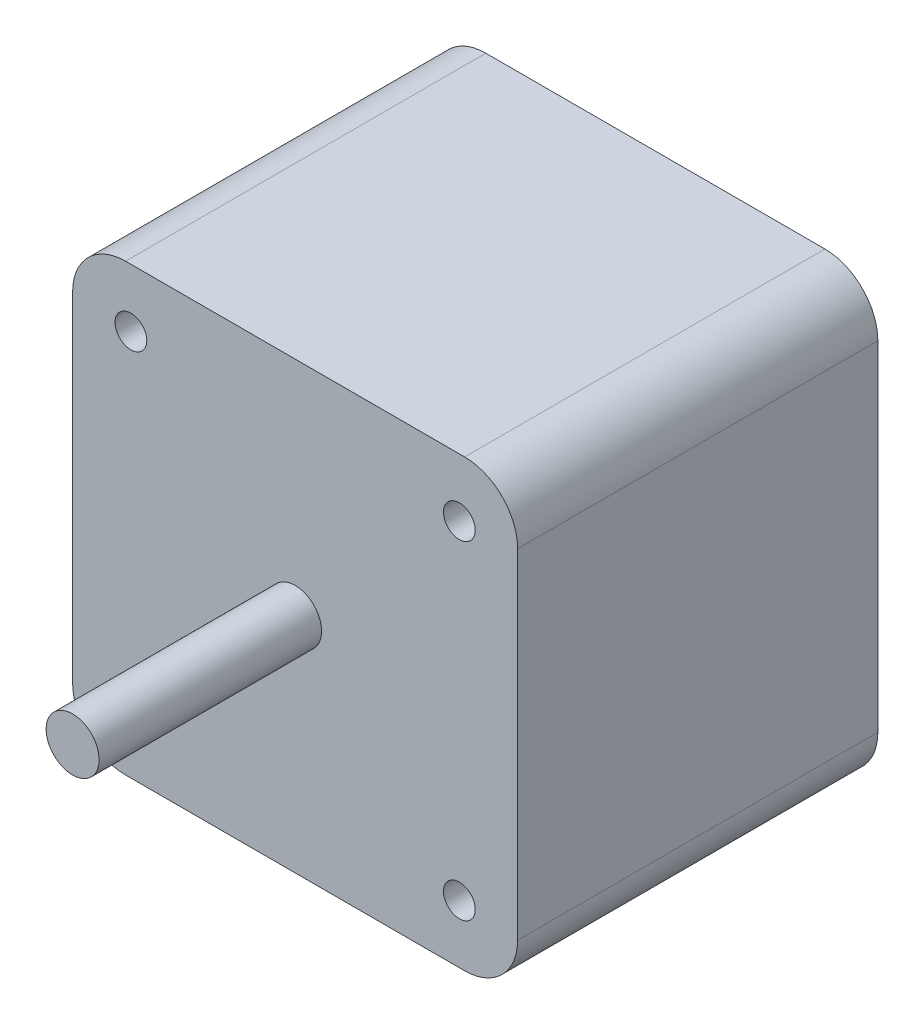
SolidWorks part; units mm, degrees
ref_plane "Płaszczyzna przednia" through (0, 0, 0) normal (0, 0, 1) x (1, 0, 0)
ref_plane "Płaszczyzna górna" through (0, 0, 0) normal (0, 1, 0) x (1, 0, 0)
ref_plane "Płaszczyzna prawa" through (0, 0, 0) normal (1, 0, 0) x (0, 0, -1)
sketch "Szkic1" plane through (0, 0, 0) normal (0, 0, 1) x (1, 0, 0)
  line L1 (-21, -21) -> (21, -21)
  line L2 (-21, -21) -> (-21, 21)
  line L3 (-21, 21) -> (21, 21)
  line L4 (21, -21) -> (21, 21)
  line L5 (-21, -21) -> (21, 21) construction
  line L6 (-21, 21) -> (21, -21) construction
  point P0 (0, 0)
extrude "Dodanie-wyciągnięcie1" add sketch "Szkic1" along normal blind 34
sketch "Szkic2" plane through (0, 0, 34) normal (0, 0, 1) x (1, 0, 0)
  circle A0 centre (15.5, 15.5) radius 1.5
extrude "Wytnij-wyciągnięcie1" cut sketch "Szkic2" against normal blind 11
sketch "Szkic6" plane through (0, 0, 34) normal (0, 0, 1) x (1, 0, 0)
  circle A0 centre (-15.5, 15.5) radius 1.5
extrude "Wytnij-wyciągnięcie2" cut sketch "Szkic6" against normal blind 11
sketch "Szkic7" plane through (0, 0, 34) normal (0, 0, 1) x (1, 0, 0)
  circle A0 centre (-15.5, -15.5) radius 1.5
extrude "Wytnij-wyciągnięcie3" cut sketch "Szkic7" against normal blind 11
sketch "Szkic8" plane through (0, 0, 34) normal (0, 0, 1) x (1, 0, 0)
  circle A0 centre (15.5, -15.5) radius 1.5
extrude "Wytnij-wyciągnięcie4" cut sketch "Szkic8" against normal blind 11
fillet "Zaokrąglenie1" radius 5 4 edges at (-21, 21, 17) (-21, -21, 17) (21, -21, 17) (21, 21, 17)
sketch "Szkic9" plane through (0, 0, 34) normal (0, 0, 1) x (1, 0, 0)
  circle A0 centre (0, 0) radius 2.5
  dimension "D1" = 5
extrude "Dodanie-wyciągnięcie4" add sketch "Szkic9" along normal blind 21
sketch "Szkic11" plane through (0, 0, 0) normal (0, 0, -1) x (-1, 0, 0)
  text T0 "NEMA 17"
extrude "Wytnij-wyciągnięcie5" cut sketch "Szkic11" against normal blind 1
